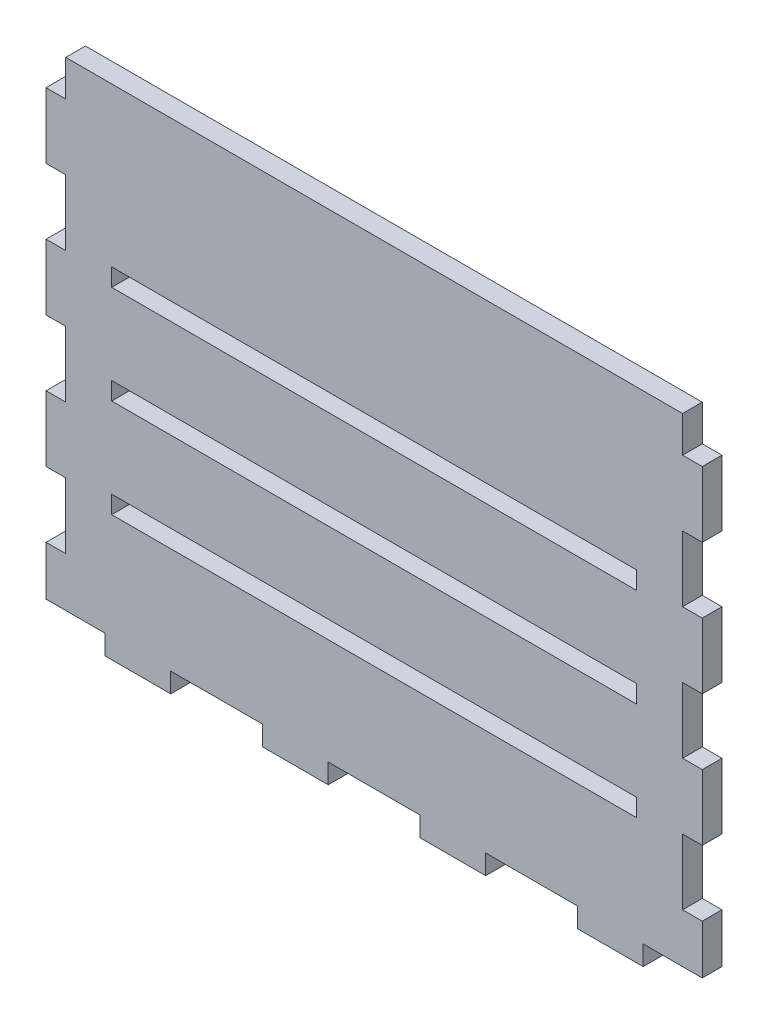
SolidWorks part; units mm, degrees
ref_plane "前基準面" through (0, 0, 0) normal (0, 0, 1) x (1, 0, 0)
ref_plane "上基準面" through (0, 0, 0) normal (0, 1, 0) x (1, 0, 0)
ref_plane "右基準面" through (0, 0, 0) normal (1, 0, 0) x (0, 0, -1)
sketch "草圖1" plane through (0, 0, 0) normal (0, 0, 1) x (1, 0, 0)
  line L0 (-11.9193, -41.7083) -> (-11.9193, -60.4731) construction
  line L1 (-61.9193, 23.7181) -> (-52.9193, 23.7181)
  line L2 (-61.9193, 23.7181) -> (-61.9193, 16.2181)
  line L3 (-61.9193, -41.2819) -> (-52.9193, -41.2819)
  line L4 (38.0807, 23.7181) -> (38.0807, 16.2181)
  line L5 (19.0807, -44.2819) -> (29.0807, -44.2819)
  line L7 (-28.9193, -41.2819) -> (-28.9193, -44.2819)
  line L8 (-28.9193, -44.2819) -> (-18.9193, -44.2819)
  line L9 (-18.9193, -41.2819) -> (-18.9193, -44.2819)
  line L11 (-42.9193, -41.2819) -> (-42.9193, -44.2819)
  line L12 (-42.9193, -44.2819) -> (-52.9193, -44.2819)
  line L13 (-52.9193, -41.2819) -> (-52.9193, -44.2819)
  line L14 (29.0807, -41.2819) -> (29.0807, -44.2819)
  line L16 (19.0807, -41.2819) -> (19.0807, -44.2819)
  line L17 (5.0807, -44.2819) -> (-4.9193, -44.2819)
  line L18 (-4.9193, -41.2819) -> (-4.9193, -44.2819)
  line L20 (5.0807, -41.2819) -> (5.0807, -44.2819)
  line L21 (-61.9193, -8.7819) -> (38.0807, -8.7819) construction
  line L23 (19.0807, 23.7181) -> (19.0807, 26.7181)
  line L25 (29.0807, 23.7181) -> (29.0807, 26.7181)
  line L26 (19.0807, 26.7181) -> (29.0807, 26.7181)
  line L27 (5.0807, 23.7181) -> (5.0807, 26.7181)
  line L29 (-4.9193, 23.7181) -> (-4.9193, 26.7181)
  line L30 (5.0807, 26.7181) -> (-4.9193, 26.7181)
  line L31 (-28.9193, 26.7181) -> (-18.9193, 26.7181)
  line L32 (-18.9193, 23.7181) -> (-18.9193, 26.7181)
  line L34 (-28.9193, 23.7181) -> (-28.9193, 26.7181)
  line L35 (-42.9193, 26.7181) -> (-52.9193, 26.7181)
  line L36 (-52.9193, 23.7181) -> (-52.9193, 26.7181)
  line L38 (-42.9193, 23.7181) -> (-42.9193, 26.7181)
  line L39 (-42.9193, 23.7181) -> (-28.9193, 23.7181)
  line L40 (-18.9193, 23.7181) -> (-4.9193, 23.7181)
  line L41 (5.0807, 23.7181) -> (19.0807, 23.7181)
  line L42 (29.0807, 23.7181) -> (38.0807, 23.7181)
  line L43 (29.0807, -41.2819) -> (38.0807, -41.2819)
  line L44 (5.0807, -41.2819) -> (19.0807, -41.2819)
  line L45 (-18.9193, -41.2819) -> (-4.9193, -41.2819)
  line L46 (-42.9193, -41.2819) -> (-28.9193, -41.2819)
  line L47 (-61.9193, -33.7819) -> (-58.9193, -33.7819)
  line L48 (-61.9193, -3.7819) -> (-58.9193, -3.7819)
  line L50 (-61.9193, -13.7819) -> (-58.9193, -13.7819)
  line L51 (-58.9193, -3.7819) -> (-58.9193, -13.7819)
  line L52 (-61.9193, 6.2181) -> (-58.9193, 6.2181)
  line L54 (-61.9193, 16.2181) -> (-58.9193, 16.2181)
  line L55 (-58.9193, 6.2181) -> (-58.9193, 16.2181)
  line L56 (-58.9193, -23.7819) -> (-58.9193, -33.7819)
  line L57 (-61.9193, -23.7819) -> (-58.9193, -23.7819)
  line L60 (38.0807, -23.7819) -> (35.0807, -23.7819)
  line L61 (35.0807, -23.7819) -> (35.0807, -33.7819)
  line L62 (38.0807, -33.7819) -> (35.0807, -33.7819)
  line L63 (38.0807, -13.7819) -> (35.0807, -13.7819)
  line L64 (35.0807, -3.7819) -> (35.0807, -13.7819)
  line L65 (38.0807, -3.7819) -> (35.0807, -3.7819)
  line L67 (38.0807, 16.2181) -> (35.0807, 16.2181)
  line L68 (35.0807, 6.2181) -> (35.0807, 16.2181)
  line L69 (38.0807, 6.2181) -> (35.0807, 6.2181)
  line L71 (-61.9193, -33.7819) -> (-61.9193, -41.2819)
  line L72 (-61.9193, -13.7819) -> (-61.9193, -23.7819)
  line L73 (-61.9193, 6.2181) -> (-61.9193, -3.7819)
  line L74 (38.0807, 6.2181) -> (38.0807, -3.7819)
  line L75 (38.0807, -13.7819) -> (38.0807, -23.7819)
  line L76 (38.0807, -33.7819) -> (38.0807, -41.2819)
  point P46 (-58.9193, -8.7819)
  dimension "D1" = 100
  dimension "D2" = 65
  dimension "D3" = 3
  dimension "D4" = 10
  dimension "D5" = 7
  dimension "D6" = 3
  dimension "D7" = 10
  dimension "D8" = 14
  dimension "D9" = 3
  dimension "D10" = 10
  dimension "D11" = 9
  dimension "D12" = 3
  dimension "D13" = 10
  dimension "D14" = 10
extrude "填料-伸長1" add sketch "草圖1" along normal blind 3
sketch "草圖2" plane through (0, 0, 0) normal (0, 0, -1) x (-1, 0, 0)
  line L0 (58.9193, -8.7819) -> (-35.0807, -8.7819) construction
  line L1 (58.9193, -3.7819) -> (58.9193, -13.7819) construction
  line L2 (-35.0807, -13.7819) -> (-35.0807, -3.7819) construction
  line L3 (11.9193, -8.7819) -> (11.9193, -23.7819) construction
  line L4 (51.9193, -10.1319) -> (-28.0807, -10.1319)
  line L5 (51.9193, -10.1319) -> (51.9193, -7.4319)
  line L6 (51.9193, -7.4319) -> (-28.0807, -7.4319)
  line L7 (-28.0807, -10.1319) -> (-28.0807, -7.4319)
  line L8 (51.9193, -10.1319) -> (-28.0807, -7.4319) construction
  line L9 (51.9193, -7.4319) -> (-28.0807, -10.1319) construction
  line L10 (51.9193, 4.8681) -> (-28.0807, 4.8681)
  line L11 (51.9193, -25.1319) -> (-28.0807, -25.1319)
  line L12 (51.9193, -25.1319) -> (51.9193, -22.4319)
  line L13 (51.9193, -22.4319) -> (-28.0807, -22.4319)
  line L14 (-28.0807, -25.1319) -> (-28.0807, -22.4319)
  line L15 (51.9193, -25.1319) -> (-28.0807, -22.4319) construction
  line L16 (51.9193, -22.4319) -> (-28.0807, -25.1319) construction
  line L17 (-28.0807, 7.5681) -> (-28.0807, 4.8681)
  line L18 (51.9193, 7.5681) -> (-28.0807, 7.5681)
  line L19 (51.9193, 7.5681) -> (51.9193, 4.8681)
  point P6 (11.9193, -8.7819)
  dimension "D1" = 2.7
  dimension "D2" = 80
  dimension "D3" = 2.7
  dimension "D4" = 80
  dimension "D5" = 15
extrude "除料-伸長1" cut sketch "草圖2" against normal blind 3
sketch "草圖3" plane through (0, 0, 3) normal (0, 0, 1) x (1, 0, 0)
  line L5 (-61.9193, 23.7181) -> (-61.9193, 16.2181) construction
  line L6 (38.0807, 23.7181) -> (-61.9193, 23.7181)
  line L7 (38.0807, 23.7181) -> (38.0807, 31.7181)
  line L8 (38.0807, 31.7181) -> (-61.9193, 31.7181)
  line L9 (-61.9193, 23.7181) -> (-61.9193, 31.7181)
  dimension "D1" = 8
extrude "填料-伸長3" add sketch "草圖3" against normal blind 3
sketch "草圖4" plane through (0, 0, 3) normal (0, 0, 1) x (1, 0, 0)
  line L0 (35.0807, 16.2181) -> (38.0807, 16.2181) construction
  line L1 (38.0807, 31.7181) -> (35.0807, 31.7181)
  line L2 (38.0807, 31.7181) -> (38.0807, 26.2181)
  line L3 (38.0807, 26.2181) -> (35.0807, 26.2181)
  line L4 (35.0807, 31.7181) -> (35.0807, 26.2181)
  line L5 (-11.9193, -41.2819) -> (-11.9193, -33.0293) construction
  line L6 (-18.9193, -41.2819) -> (-4.9193, -41.2819) construction
  line L7 (-61.9193, 26.2181) -> (-58.9193, 26.2181)
  line L8 (-58.9193, 31.7181) -> (-58.9193, 26.2181)
  line L9 (-61.9193, 31.7181) -> (-58.9193, 31.7181)
  line L10 (-61.9193, 31.7181) -> (-61.9193, 26.2181)
  dimension "D1" = 3
  dimension "D2" = 10
extrude "除料-伸長2" cut sketch "草圖4" against normal blind 3
